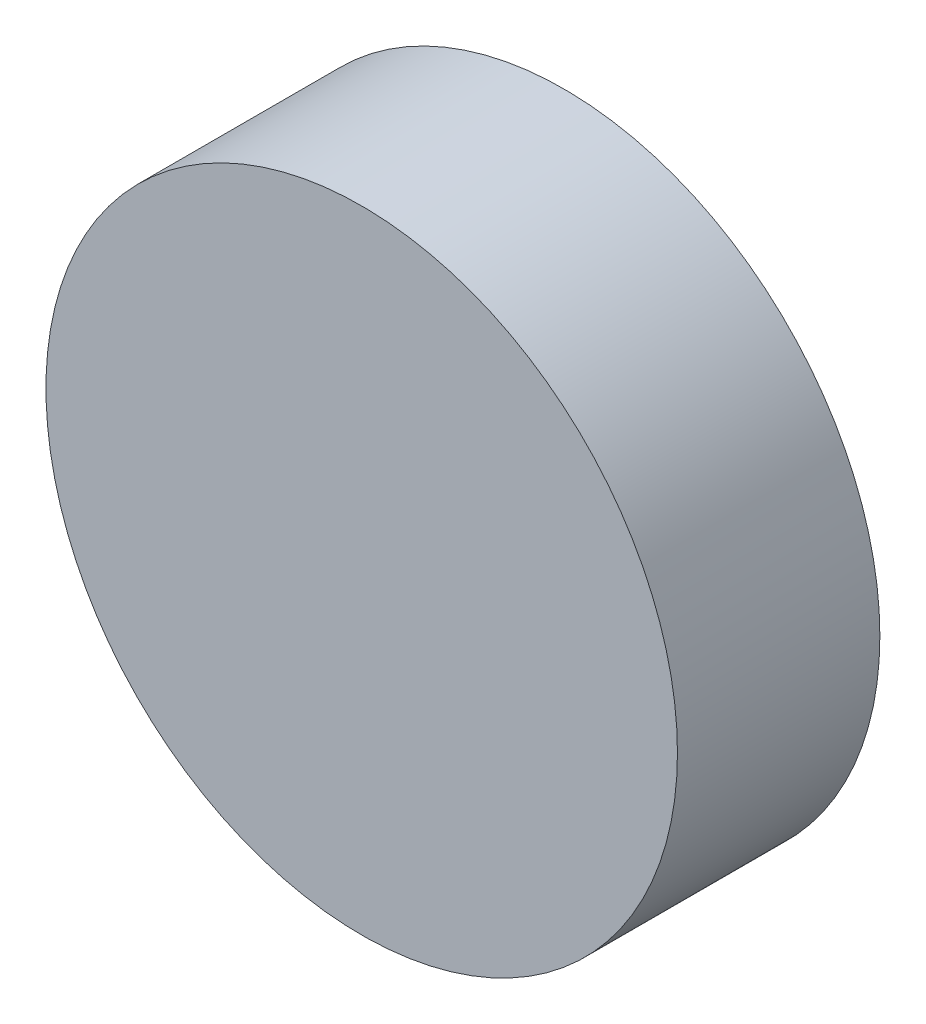
SolidWorks part; units mm, degrees
ref_plane "Front Plane" through (0, 0, 0) normal (0, 0, 1) x (1, 0, 0)
ref_plane "Top Plane" through (0, 0, 0) normal (0, 1, 0) x (1, 0, 0)
ref_plane "Right Plane" through (0, 0, 0) normal (1, 0, 0) x (0, 0, -1)
sketch "Croquis1" plane through (0, 0, 0) normal (0, 0, 1) x (1, 0, 0)
  circle A0 centre (0, 0) radius 31.2
  dimension "D1" = 62.4
extrude "Saliente-Extruir1" add sketch "Croquis1" along normal blind 20
